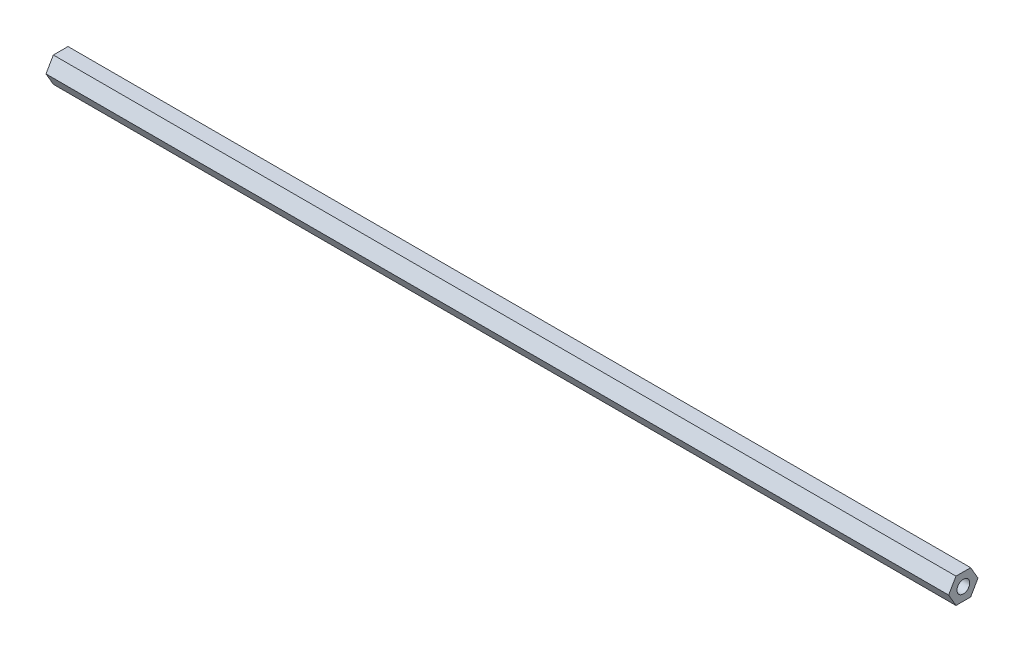
SolidWorks part; units mm, degrees
material "7075-T6 (SN)"
ref_plane "Front Plane" through (0, 0, 0) normal (0, 0, 1) x (1, 0, 0)
ref_plane "Top Plane" through (0, 0, 0) normal (0, 1, 0) x (1, 0, 0)
ref_plane "Right Plane" through (0, 0, 0) normal (1, 0, 0) x (0, 0, -1)
sketch "Sketch1" plane through (0, 0, 0) normal (1, 0, 0) x (0, 0, -1)
  line L1 (-3.6662, 6.35) -> (-7.3323, 0)
  line L2 (-7.3323, 0) -> (-3.6662, -6.35)
  line L3 (-3.6662, -6.35) -> (3.6662, -6.35)
  line L4 (3.6662, -6.35) -> (7.3323, 0)
  line L5 (7.3323, 0) -> (3.6662, 6.35)
  line L6 (3.6662, 6.35) -> (-3.6662, 6.35)
  circle A0 centre (0, 0) radius 6.35 construction
  circle A1 centre (0, 0) radius 3.175
  dimension "D2" = 6.35
  dimension "D1" = 12.7
extrude "Boss-Extrude1" add sketch "Sketch1" along normal mid plane 450.85
